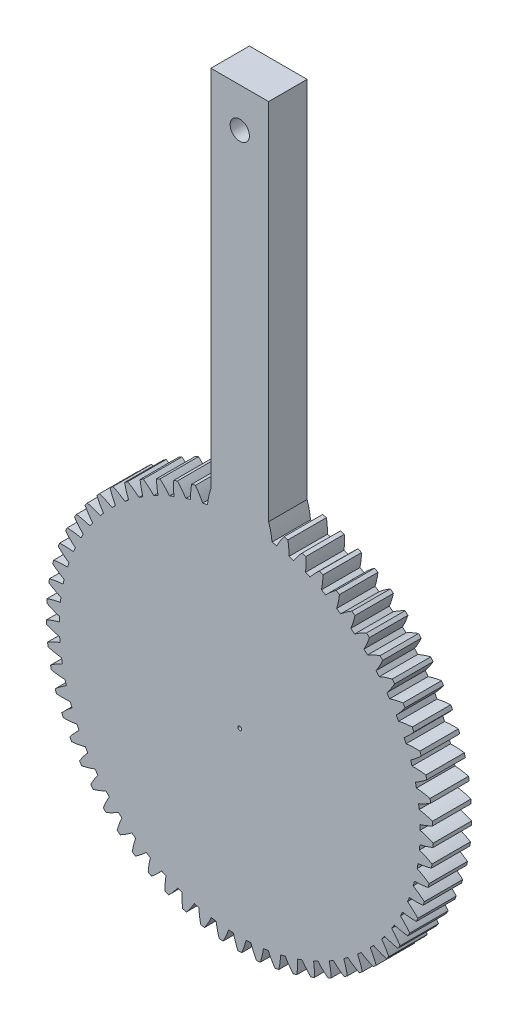
SolidWorks part; units mm, degrees
material "Acrylic (Medium-high impact)"
ref_plane "Front Plane" through (0, 0, 0) normal (0, 0, 1) x (1, 0, 0)
ref_plane "Top Plane" through (0, 0, 0) normal (0, 1, 0) x (1, 0, 0)
ref_plane "Right Plane" through (0, 0, 0) normal (1, 0, 0) x (0, 0, -1)
sketch "Sketch1" plane through (0, 0, 0) normal (0, 0, 1) x (1, 0, 0)
  line L0 (-7.5, 144.81) -> (7.5, 144.81)
  line L1 (7.5, 144.81) -> (7.5, 50.2519)
  line L2 (-7.5, 144.81) -> (-7.5, 50.2519)
  circle A0 centre (0, 0) radius 50.8085 construction
  arc A12 (-7.5, 50.2519) -> (-8.3908, 46.1211) centre (11.0117, 44.0987) ccw
  arc A13 (-8.3908, 46.1211) -> (-9.6207, 45.8803) centre (0, 0) ccw
  arc A14 (-9.6207, 45.8803) -> (-11.5392, 48.9109) centre (-26.9927, 37.0057) ccw
  arc A15 (-11.5392, 48.9109) -> (-12.5126, 48.671) centre (0, 0) ccw
  arc A16 (-12.5126, 48.671) -> (-12.8029, 45.0959) centre (6.7035, 45.3111) ccw
  arc A17 (-12.8029, 45.0959) -> (-14.0039, 44.7376) centre (0, 0) ccw
  arc A18 (-14.0039, 44.7376) -> (-16.206, 47.5689) centre (-30.4383, 34.2278) ccw
  arc A19 (-16.206, 47.5689) -> (-17.1516, 47.2362) centre (0, 0) ccw
  arc A20 (-17.1516, 47.2362) -> (-17.0955, 43.6498) centre (2.299, 45.7465) ccw
  arc A21 (-17.0955, 43.6498) -> (-18.2563, 43.1771) centre (0, 0) ccw
  arc A22 (-18.2563, 43.1771) -> (-20.7214, 45.7827) centre (-33.5997, 31.1303) ccw
  arc A23 (-20.7214, 45.7827) -> (-21.6305, 45.3603) centre (0, 0) ccw
  arc A24 (-21.6305, 45.3603) -> (-21.2285, 41.796) centre (-2.1269, 45.7549) ccw
  arc A25 (-21.2285, 41.796) -> (-22.3383, 41.2136) centre (0, 0) ccw
  arc A26 (-22.3383, 41.2136) -> (-25.0433, 43.5691) centre (-36.4473, 27.7421) ccw
  arc A27 (-25.0433, 43.5691) -> (-25.9074, 43.0609) centre (0, 0) ccw
  arc A28 (-25.9074, 43.0609) -> (-25.1633, 39.5521) centre (-6.5329, 45.336) ccw
  arc A29 (-25.1633, 39.5521) -> (-26.2117, 38.8652) centre (0, 0) ccw
  arc A30 (-26.2117, 38.8652) -> (-29.1314, 40.9487) centre (-38.9547, 24.0949) ccw
  arc A31 (-29.1314, 40.9487) -> (-29.9424, 40.3595) centre (0, 0) ccw
  arc A32 (-29.9424, 40.3595) -> (-28.8632, 36.9388) centre (-10.878, 44.4938) ccw
  arc A33 (-28.8632, 36.9388) -> (-29.8404, 36.154) centre (0, 0) ccw
  arc A34 (-29.8404, 36.154) -> (-32.9475, 37.9459) centre (-41.0983, 20.2228) ccw
  arc A35 (-32.9475, 37.9459) -> (-33.6979, 37.2812) centre (0, 0) ccw
  arc A36 (-33.6979, 37.2812) -> (-32.2935, 33.9807) centre (-15.1215, 43.2362) ccw
  arc A37 (-32.2935, 33.9807) -> (-33.1904, 33.1052) centre (0, 0) ccw
  arc A38 (-33.1904, 33.1052) -> (-36.456, 34.5889) centre (-42.8582, 16.1618) ccw
  arc A39 (-36.456, 34.5889) -> (-37.1387, 33.8548) centre (0, 0) ccw
  arc A40 (-37.1387, 33.8548) -> (-35.4224, 30.7053) centre (-19.2238, 41.575) ccw
  arc A41 (-35.4224, 30.7053) -> (-36.2306, 29.7473) centre (0, 0) ccw
  arc A42 (-36.2306, 29.7473) -> (-39.6242, 30.9089) centre (-44.218, 11.95) ccw
  arc A43 (-39.6242, 30.9089) -> (-40.2328, 30.1124) centre (0, 0) ccw
  arc A44 (-40.2328, 30.1124) -> (-38.2205, 27.1432) centre (-23.1466, 39.5255) ccw
  arc A45 (-38.2205, 27.1432) -> (-38.9325, 26.1117) centre (0, 0) ccw
  arc A46 (-38.9325, 26.1117) -> (-42.4223, 26.9403) centre (-45.1649, 7.6265) ccw
  arc A47 (-42.4223, 26.9403) -> (-42.9513, 26.0888) centre (0, 0) ccw
  arc A48 (-42.9513, 26.0888) -> (-40.6618, 23.3276) centre (-26.8533, 37.107) ccw
  arc A49 (-40.6618, 23.3276) -> (-41.2709, 22.2323) centre (0, 0) ccw
  arc A50 (-41.2709, 22.2323) -> (-44.8244, 22.7202) centre (-45.6901, 3.2319) ccw
  arc A51 (-44.8244, 22.7202) -> (-45.2687, 21.8216) centre (0, 0) ccw
  arc A52 (-45.2687, 21.8216) -> (-42.7234, 19.2943) centre (-30.3093, 34.3421) ccw
  arc A53 (-42.7234, 19.2943) -> (-43.2239, 18.1453) centre (0, 0) ccw
  arc A54 (-43.2239, 18.1453) -> (-46.808, 18.288) centre (-45.7887, -1.1929) ccw
  arc A55 (-46.808, 18.288) -> (-47.1634, 17.3507) centre (0, 0) ccw
  arc A56 (-47.1634, 17.3507) -> (-44.3861, 15.0808) centre (-33.4823, 31.2565) ccw
  arc A57 (-44.3861, 15.0808) -> (-44.7734, 13.8889) centre (0, 0) ccw
  arc A58 (-44.7734, 13.8889) -> (-48.3545, 13.685) centre (-45.4598, -5.6066) ccw
  arc A59 (-48.3545, 13.685) -> (-48.6178, 12.7177) centre (0, 0) ccw
  arc A60 (-48.6178, 12.7177) -> (-45.6344, 10.7266) centre (-36.3427, 27.8791) ccw
  arc A61 (-45.6344, 10.7266) -> (-45.9049, 9.5028) centre (0, 0) ccw
  arc A62 (-45.9049, 9.5028) -> (-49.4495, 8.9542) centre (-44.7065, -9.968) ccw
  arc A63 (-49.4495, 8.9542) -> (-49.6183, 7.9661) centre (0, 0) ccw
  arc A64 (-49.6183, 7.9661) -> (-46.4566, 6.2721) centre (-38.8637, 24.2413) ccw
  arc A65 (-46.4566, 6.2721) -> (-46.6077, 5.0279) centre (0, 0) ccw
  arc A66 (-46.6077, 5.0279) -> (-50.0829, 4.1398) centre (-43.5358, -14.2362) ccw
  arc A67 (-50.0829, 4.1398) -> (-50.1555, 3.14) centre (0, 0) ccw
  arc A68 (-50.1555, 3.14) -> (-46.8451, 1.7591) centre (-41.0219, 20.3773) ccw
  arc A69 (-46.8451, 1.7591) -> (-46.8754, 0.5062) centre (0, 0) ccw
  arc A70 (-46.8754, 0.5062) -> (-50.2486, -0.7132) centre (-41.9585, -18.3716) ccw
  arc A71 (-50.2486, -0.7132) -> (-50.2244, -1.7153) centre (0, 0) ccw
  arc A72 (-50.2244, -1.7153) -> (-46.7962, -2.7703) centre (-42.7971, 16.323) ccw
  arc A73 (-46.7962, -2.7703) -> (-46.7054, -4.0203) centre (0, 0) ccw
  arc A74 (-46.7054, -4.0203) -> (-49.9452, -5.5595) centre (-39.9895, -22.3354) ccw
  arc A75 (-49.9452, -5.5595) -> (-49.8244, -6.5547) centre (0, 0) ccw
  arc A76 (-49.8244, -6.5547) -> (-46.3104, -7.2738) centre (-44.1727, 12.1162) ccw
  arc A77 (-46.3104, -7.2738) -> (-46.0994, -8.5093) centre (0, 0) ccw
  arc A78 (-46.0994, -8.5093) -> (-49.1755, -10.354) centre (-37.6472, -26.0907) ccw
  arc A79 (-49.1755, -10.354) -> (-48.9592, -11.3328) centre (0, 0) ccw
  arc A80 (-48.9592, -11.3328) -> (-45.3921, -11.7095) centre (-45.1359, 7.7964) ccw
  arc A81 (-45.3921, -11.7095) -> (-45.0629, -12.9188) centre (0, 0) ccw
  arc A82 (-45.0629, -12.9188) -> (-47.9466, -15.0518) centre (-34.9533, -29.6023) ccw
  arc A83 (-47.9466, -15.0518) -> (-47.6369, -16.0052) centre (0, 0) ccw
  arc A84 (-47.6369, -16.0052) -> (-44.0501, -16.0358) centre (-45.6776, 3.4038) ccw
  arc A85 (-44.0501, -16.0358) -> (-43.6057, -17.2077) centre (0, 0) ccw
  arc A86 (-43.6057, -17.2077) -> (-46.2701, -19.609) centre (-31.9331, -32.8376) ccw
  arc A87 (-46.2701, -19.609) -> (-45.8697, -20.5281) centre (0, 0) ccw
  arc A88 (-45.8697, -20.5281) -> (-42.2968, -20.2124) centre (-45.7929, -1.0207) ccw
  arc A89 (-42.2968, -20.2124) -> (-41.7413, -21.3359) centre (0, 0) ccw
  arc A90 (-41.7413, -21.3359) -> (-44.1615, -23.9832) centre (-28.6147, -35.7663) ccw
  arc A91 (-44.1615, -23.9832) -> (-43.6744, -24.8593) centre (0, 0) ccw
  arc A92 (-43.6744, -24.8593) -> (-40.1486, -24.2003) centre (-45.4806, -5.4356) ccw
  arc A93 (-40.1486, -24.2003) -> (-39.4873, -25.2649) centre (0, 0) ccw
  arc A94 (-39.4873, -25.2649) -> (-41.6407, -28.1334) centre (-25.0292, -38.3611) ccw
  arc A95 (-41.6407, -28.1334) -> (-41.0712, -28.9584) centre (0, 0) ccw
  arc A96 (-41.0712, -28.9584) -> (-37.6255, -27.9622) centre (-44.7437, -9.7997) ccw
  arc A97 (-37.6255, -27.9622) -> (-36.8645, -28.958) centre (0, 0) ccw
  arc A98 (-36.8645, -28.958) -> (-38.731, -32.021) centre (-21.21, -40.5976) ccw
  arc A99 (-38.731, -32.021) -> (-38.0846, -32.7872) centre (0, 0) ccw
  arc A100 (-38.0846, -32.7872) -> (-34.7511, -31.463) centre (-43.589, -14.0723) ccw
  arc A101 (-34.7511, -31.463) -> (-33.8976, -32.3808) centre (0, 0) ccw
  arc A102 (-33.8976, -32.3808) -> (-35.4597, -35.6096) centre (-17.1927, -42.4552) ccw
  arc A103 (-35.4597, -35.6096) -> (-34.7424, -36.3098) centre (0, 0) ccw
  arc A104 (-34.7424, -36.3098) -> (-31.5522, -34.6701) centre (-42.0273, -18.2136) ccw
  arc A105 (-31.5522, -34.6701) -> (-30.6141, -35.5012) centre (0, 0) ccw
  arc A106 (-30.6141, -35.5012) -> (-31.8574, -38.8657) centre (-13.0149, -43.9163) ccw
  arc A107 (-31.8574, -38.8657) -> (-31.0758, -39.4934) centre (0, 0) ccw
  arc A108 (-31.0758, -39.4934) -> (-28.0588, -37.5535) centre (-40.0733, -22.1848) ccw
  arc A109 (-28.0588, -37.5535) -> (-27.0448, -38.2902) centre (0, 0) ccw
  arc A110 (-27.0448, -38.2902) -> (-27.9575, -41.759) centre (-8.7157, -44.9674) ccw
  arc A111 (-27.9575, -41.759) -> (-27.119, -42.3083) centre (0, 0) ccw
  arc A112 (-27.119, -42.3083) -> (-24.3034, -40.0862) centre (-37.7451, -25.9488) ccw
  arc A113 (-24.3034, -40.0862) -> (-23.223, -40.7216) centre (0, 0) ccw
  arc A114 (-23.223, -40.7216) -> (-23.7967, -44.2623) centre (-4.335, -45.5987) ccw
  arc A115 (-23.7967, -44.2623) -> (-22.9091, -44.7282) centre (0, 0) ccw
  arc A116 (-22.9091, -44.7282) -> (-20.321, -42.2447) centre (-35.0644, -29.4706) ccw
  arc A117 (-20.321, -42.2447) -> (-19.1844, -42.7728) centre (0, 0) ccw
  arc A118 (-19.1844, -42.7728) -> (-19.4137, -46.3524) centre (0.0862, -45.8042) ccw
  arc A119 (-19.4137, -46.3524) -> (-18.4853, -46.7304) centre (0, 0) ccw
  arc A120 (-18.4853, -46.7304) -> (-16.149, -44.0087) centre (-32.0564, -32.7173) ccw
  arc A121 (-16.149, -44.0087) -> (-14.9667, -44.4247) centre (0, 0) ccw
  arc A122 (-14.9667, -44.4247) -> (-14.8494, -48.0097) centre (4.5065, -45.5821) ccw
  arc A123 (-14.8494, -48.0097) -> (-13.8888, -48.2963) centre (0, 0) ccw
  arc A124 (-13.8888, -48.2963) -> (-11.8261, -45.3619) centre (-28.7491, -35.6584) ccw
  arc A125 (-11.8261, -45.3619) -> (-10.6092, -45.6618) centre (0, 0) ccw
  arc A126 (-10.6092, -45.6618) -> (-10.1465, -49.2187) centre (8.8848, -44.9343) ccw
  arc A127 (-10.1465, -49.2187) -> (-9.1627, -49.4113) centre (0, 0) ccw
  arc A128 (-9.1627, -49.4113) -> (-7.3929, -46.2915) centre (-25.1733, -38.2666) ccw
  arc A129 (-7.3929, -46.2915) -> (-6.1527, -46.4726) centre (0, 0) ccw
  arc A130 (-6.1527, -46.4726) -> (-5.3488, -49.9682) centre (13.1801, -43.867) ccw
  arc A131 (-5.3488, -49.9682) -> (-4.3511, -50.065) centre (0, 0) ccw
  arc A132 (-4.3511, -50.065) -> (-2.8906, -46.7889) centre (-21.3626, -40.5176) ccw
  arc A133 (-2.8906, -46.7889) -> (-1.6387, -46.8495) centre (0, 0) ccw
  arc A134 (-1.6387, -46.8495) -> (-0.5012, -50.2512) centre (17.3523, -42.3902) ccw
  arc A135 (-0.5012, -50.2512) -> (0.5012, -50.2512) centre (0, 0) ccw
  arc A136 (0.5012, -50.2512) -> (1.6387, -46.8495) centre (-17.3523, -42.3902) ccw
  arc A137 (1.6387, -46.8495) -> (2.8906, -46.7889) centre (0, 0) ccw
  arc A138 (2.8906, -46.7889) -> (4.3511, -50.065) centre (21.3626, -40.5176) ccw
  arc A139 (4.3511, -50.065) -> (5.3488, -49.9682) centre (0, 0) ccw
  arc A140 (5.3488, -49.9682) -> (6.1527, -46.4726) centre (-13.1801, -43.867) ccw
  arc A141 (6.1527, -46.4726) -> (7.3929, -46.2915) centre (0, 0) ccw
  arc A142 (7.3929, -46.2915) -> (9.1627, -49.4113) centre (25.1733, -38.2666) ccw
  arc A143 (9.1627, -49.4113) -> (10.1465, -49.2187) centre (0, 0) ccw
  arc A144 (10.1465, -49.2187) -> (10.6092, -45.6618) centre (-8.8848, -44.9343) ccw
  arc A145 (10.6092, -45.6618) -> (11.8261, -45.3619) centre (0, 0) ccw
  arc A146 (11.8261, -45.3619) -> (13.8888, -48.2963) centre (28.7491, -35.6584) ccw
  arc A147 (13.8888, -48.2963) -> (14.8494, -48.0097) centre (0, 0) ccw
  arc A148 (14.8494, -48.0097) -> (14.9667, -44.4247) centre (-4.5065, -45.5821) ccw
  arc A149 (14.9667, -44.4247) -> (16.149, -44.0087) centre (0, 0) ccw
  arc A150 (16.149, -44.0087) -> (18.4853, -46.7304) centre (32.0564, -32.7173) ccw
  arc A151 (18.4853, -46.7304) -> (19.4137, -46.3524) centre (0, 0) ccw
  arc A152 (19.4137, -46.3524) -> (19.1844, -42.7728) centre (-0.0862, -45.8042) ccw
  arc A153 (19.1844, -42.7728) -> (20.321, -42.2447) centre (0, 0) ccw
  arc A154 (20.321, -42.2447) -> (22.9091, -44.7282) centre (35.0644, -29.4706) ccw
  arc A155 (22.9091, -44.7282) -> (23.7967, -44.2623) centre (0, 0) ccw
  arc A156 (23.7967, -44.2623) -> (23.223, -40.7216) centre (4.335, -45.5987) ccw
  arc A157 (23.223, -40.7216) -> (24.3034, -40.0862) centre (0, 0) ccw
  arc A158 (24.3034, -40.0862) -> (27.119, -42.3083) centre (37.7451, -25.9488) ccw
  arc A159 (27.119, -42.3083) -> (27.9575, -41.759) centre (0, 0) ccw
  arc A160 (27.9575, -41.759) -> (27.0448, -38.2902) centre (8.7157, -44.9674) ccw
  arc A161 (27.0448, -38.2902) -> (28.0588, -37.5535) centre (0, 0) ccw
  arc A162 (28.0588, -37.5535) -> (31.0758, -39.4934) centre (40.0733, -22.1848) ccw
  arc A163 (31.0758, -39.4934) -> (31.8574, -38.8657) centre (0, 0) ccw
  arc A164 (31.8574, -38.8657) -> (30.6141, -35.5012) centre (13.0149, -43.9163) ccw
  arc A165 (30.6141, -35.5012) -> (31.5522, -34.6701) centre (0, 0) ccw
  arc A166 (31.5522, -34.6701) -> (34.7424, -36.3098) centre (42.0273, -18.2136) ccw
  arc A167 (34.7424, -36.3098) -> (35.4597, -35.6096) centre (0, 0) ccw
  arc A168 (35.4597, -35.6096) -> (33.8976, -32.3808) centre (17.1927, -42.4552) ccw
  arc A169 (33.8976, -32.3808) -> (34.7511, -31.463) centre (0, 0) ccw
  arc A170 (34.7511, -31.463) -> (38.0846, -32.7872) centre (43.589, -14.0723) ccw
  arc A171 (38.0846, -32.7872) -> (38.731, -32.021) centre (0, 0) ccw
  arc A172 (38.731, -32.021) -> (36.8645, -28.958) centre (21.21, -40.5976) ccw
  arc A173 (36.8645, -28.958) -> (37.6255, -27.9622) centre (0, 0) ccw
  arc A174 (37.6255, -27.9622) -> (41.0712, -28.9584) centre (44.7437, -9.7997) ccw
  arc A175 (41.0712, -28.9584) -> (41.6407, -28.1334) centre (0, 0) ccw
  arc A176 (41.6407, -28.1334) -> (39.4873, -25.2649) centre (25.0292, -38.3611) ccw
  arc A177 (39.4873, -25.2649) -> (40.1486, -24.2003) centre (0, 0) ccw
  arc A178 (40.1486, -24.2003) -> (43.6744, -24.8593) centre (45.4806, -5.4356) ccw
  arc A179 (43.6744, -24.8593) -> (44.1615, -23.9832) centre (0, 0) ccw
  arc A180 (44.1615, -23.9832) -> (41.7413, -21.3359) centre (28.6147, -35.7663) ccw
  arc A181 (41.7413, -21.3359) -> (42.2968, -20.2124) centre (0, 0) ccw
  arc A182 (42.2968, -20.2124) -> (45.8697, -20.5281) centre (45.7929, -1.0207) ccw
  arc A183 (45.8697, -20.5281) -> (46.2701, -19.609) centre (0, 0) ccw
  arc A184 (46.2701, -19.609) -> (43.6057, -17.2077) centre (31.9331, -32.8376) ccw
  arc A185 (43.6057, -17.2077) -> (44.0501, -16.0358) centre (0, 0) ccw
  arc A186 (44.0501, -16.0358) -> (47.6369, -16.0052) centre (45.6776, 3.4038) ccw
  arc A187 (47.6369, -16.0052) -> (47.9466, -15.0518) centre (0, 0) ccw
  arc A188 (47.9466, -15.0518) -> (45.0629, -12.9188) centre (34.9533, -29.6023) ccw
  arc A189 (45.0629, -12.9188) -> (45.3921, -11.7095) centre (0, 0) ccw
  arc A190 (45.3921, -11.7095) -> (48.9592, -11.3328) centre (45.1359, 7.7964) ccw
  arc A191 (48.9592, -11.3328) -> (49.1755, -10.354) centre (0, 0) ccw
  arc A192 (49.1755, -10.354) -> (46.0994, -8.5093) centre (37.6472, -26.0907) ccw
  arc A193 (46.0994, -8.5093) -> (46.3104, -7.2738) centre (0, 0) ccw
  arc A194 (46.3104, -7.2738) -> (49.8244, -6.5547) centre (44.1727, 12.1162) ccw
  arc A195 (49.8244, -6.5547) -> (49.9452, -5.5595) centre (0, 0) ccw
  arc A196 (49.9452, -5.5595) -> (46.7054, -4.0203) centre (39.9895, -22.3354) ccw
  arc A197 (46.7054, -4.0203) -> (46.7962, -2.7703) centre (0, 0) ccw
  arc A198 (46.7962, -2.7703) -> (50.2244, -1.7153) centre (42.7971, 16.323) ccw
  arc A199 (50.2244, -1.7153) -> (50.2486, -0.7132) centre (0, 0) ccw
  arc A200 (50.2486, -0.7132) -> (46.8754, 0.5062) centre (41.9585, -18.3716) ccw
  arc A201 (46.8754, 0.5062) -> (46.8451, 1.7591) centre (0, 0) ccw
  arc A202 (46.8451, 1.7591) -> (50.1555, 3.14) centre (41.0219, 20.3773) ccw
  arc A203 (50.1555, 3.14) -> (50.0829, 4.1398) centre (0, 0) ccw
  arc A204 (50.0829, 4.1398) -> (46.6077, 5.0279) centre (43.5358, -14.2362) ccw
  arc A205 (46.6077, 5.0279) -> (46.4566, 6.2721) centre (0, 0) ccw
  arc A206 (46.4566, 6.2721) -> (49.6183, 7.9661) centre (38.8637, 24.2413) ccw
  arc A207 (49.6183, 7.9661) -> (49.4495, 8.9542) centre (0, 0) ccw
  arc A208 (49.4495, 8.9542) -> (45.9049, 9.5028) centre (44.7065, -9.968) ccw
  arc A209 (45.9049, 9.5028) -> (45.6344, 10.7266) centre (0, 0) ccw
  arc A210 (45.6344, 10.7266) -> (48.6178, 12.7177) centre (36.3427, 27.8791) ccw
  arc A211 (48.6178, 12.7177) -> (48.3545, 13.685) centre (0, 0) ccw
  arc A212 (48.3545, 13.685) -> (44.7734, 13.8889) centre (45.4598, -5.6066) ccw
  arc A213 (44.7734, 13.8889) -> (44.3861, 15.0808) centre (0, 0) ccw
  arc A214 (44.3861, 15.0808) -> (47.1634, 17.3507) centre (33.4823, 31.2565) ccw
  arc A215 (47.1634, 17.3507) -> (46.808, 18.288) centre (0, 0) ccw
  arc A216 (46.808, 18.288) -> (43.2239, 18.1453) centre (45.7887, -1.1929) ccw
  arc A217 (43.2239, 18.1453) -> (42.7234, 19.2943) centre (0, 0) ccw
  arc A218 (42.7234, 19.2943) -> (45.2687, 21.8216) centre (30.3093, 34.3421) ccw
  arc A219 (45.2687, 21.8216) -> (44.8244, 22.7202) centre (0, 0) ccw
  arc A220 (44.8244, 22.7202) -> (41.2709, 22.2323) centre (45.6901, 3.2319) ccw
  arc A221 (41.2709, 22.2323) -> (40.6618, 23.3276) centre (0, 0) ccw
  arc A222 (40.6618, 23.3276) -> (42.9513, 26.0888) centre (26.8533, 37.107) ccw
  arc A223 (42.9513, 26.0888) -> (42.4223, 26.9403) centre (0, 0) ccw
  arc A224 (42.4223, 26.9403) -> (38.9325, 26.1117) centre (45.1649, 7.6265) ccw
  arc A225 (38.9325, 26.1117) -> (38.2205, 27.1432) centre (0, 0) ccw
  arc A226 (38.2205, 27.1432) -> (40.2328, 30.1124) centre (23.1466, 39.5255) ccw
  arc A227 (40.2328, 30.1124) -> (39.6242, 30.9089) centre (0, 0) ccw
  arc A228 (39.6242, 30.9089) -> (36.2306, 29.7473) centre (44.218, 11.95) ccw
  arc A229 (36.2306, 29.7473) -> (35.4224, 30.7053) centre (0, 0) ccw
  arc A230 (35.4224, 30.7053) -> (37.1387, 33.8548) centre (19.2238, 41.575) ccw
  arc A231 (37.1387, 33.8548) -> (36.456, 34.5889) centre (0, 0) ccw
  arc A232 (36.456, 34.5889) -> (33.1904, 33.1052) centre (42.8582, 16.1618) ccw
  arc A233 (33.1904, 33.1052) -> (32.2935, 33.9807) centre (0, 0) ccw
  arc A234 (32.2935, 33.9807) -> (33.6979, 37.2812) centre (15.1215, 43.2362) ccw
  arc A235 (33.6979, 37.2812) -> (32.9475, 37.9459) centre (0, 0) ccw
  arc A236 (32.9475, 37.9459) -> (29.8404, 36.154) centre (41.0983, 20.2228) ccw
  arc A237 (29.8404, 36.154) -> (28.8632, 36.9388) centre (0, 0) ccw
  arc A238 (28.8632, 36.9388) -> (29.9424, 40.3595) centre (10.878, 44.4938) ccw
  arc A239 (29.9424, 40.3595) -> (29.1314, 40.9487) centre (0, 0) ccw
  arc A240 (29.1314, 40.9487) -> (26.2117, 38.8652) centre (38.9547, 24.0949) ccw
  arc A241 (26.2117, 38.8652) -> (25.1633, 39.5521) centre (0, 0) ccw
  arc A242 (25.1633, 39.5521) -> (25.9074, 43.0609) centre (6.5329, 45.336) ccw
  arc A243 (25.9074, 43.0609) -> (25.0433, 43.5691) centre (0, 0) ccw
  arc A244 (25.0433, 43.5691) -> (22.3383, 41.2136) centre (36.4473, 27.7421) ccw
  arc A245 (22.3383, 41.2136) -> (21.2285, 41.796) centre (0, 0) ccw
  arc A246 (21.2285, 41.796) -> (21.6305, 45.3603) centre (2.1269, 45.7549) ccw
  arc A247 (21.6305, 45.3603) -> (20.7214, 45.7827) centre (0, 0) ccw
  arc A248 (20.7214, 45.7827) -> (18.2563, 43.1771) centre (33.5997, 31.1303) ccw
  arc A249 (18.2563, 43.1771) -> (17.0955, 43.6498) centre (0, 0) ccw
  arc A250 (17.0955, 43.6498) -> (17.1516, 47.2362) centre (-2.299, 45.7465) ccw
  arc A251 (17.1516, 47.2362) -> (16.206, 47.5689) centre (0, 0) ccw
  arc A252 (16.206, 47.5689) -> (14.0039, 44.7376) centre (30.4383, 34.2278) ccw
  arc A253 (14.0039, 44.7376) -> (12.8029, 45.0959) centre (0, 0) ccw
  arc A254 (12.8029, 45.0959) -> (12.5126, 48.671) centre (-6.7035, 45.3111) ccw
  arc A255 (12.5126, 48.671) -> (11.5392, 48.9109) centre (0, 0) ccw
  arc A256 (11.5392, 48.9109) -> (9.6207, 45.8803) centre (26.9927, 37.0057) ccw
  arc A257 (9.6207, 45.8803) -> (8.3908, 46.1211) centre (0, 0) ccw
  arc A258 (8.3908, 46.1211) -> (7.5, 50.2519) centre (-11.0117, 44.0987) ccw
  dimension "D1" = 19.5076
  dimension "D2" = 15
  dimension "D3" = 19.5076
  dimension "D4" = 101.617
  dimension "D5" = 144.81
extrude "Boss-Extrude1" add sketch "Sketch1" along normal blind 10
sketch "Sketch2" plane through (0, 0, 10) normal (0, 0, 1) x (1, 0, 0)
  circle A0 centre (0, 134.62) radius 2.5
  circle A1 centre (0, 0) radius 0.5
  dimension "D1" = 5
  dimension "D3" = 1
  dimension "D2" = 134.62
extrude "Cut-Extrude1" cut sketch "Sketch2" against normal up to next
